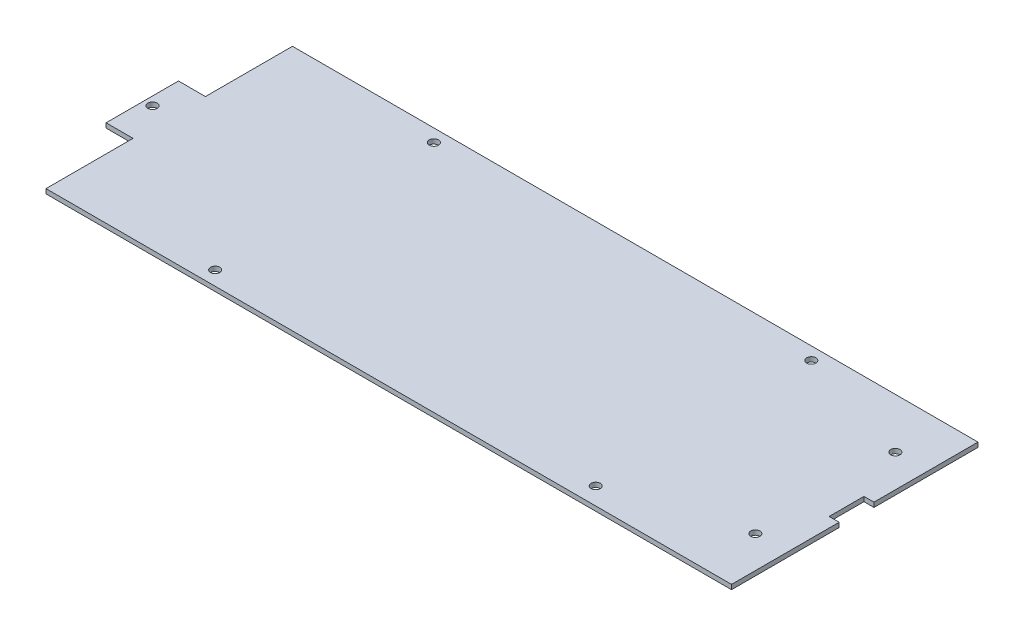
SolidWorks part; units mm, degrees
ref_plane "Front Plane" through (0, 0, 0) normal (0, 0, 1) x (1, 0, 0)
ref_plane "Top Plane" through (0, 0, 0) normal (0, 1, 0) x (1, 0, 0)
ref_plane "Right Plane" through (0, 0, 0) normal (1, 0, 0) x (0, 0, -1)
sketch "Sketch1" plane through (0, 0, 0) normal (0, 1, 0) x (1, 0, 0)
  line L0 (-302.2355, -755.753) -> (-284.7355, -755.753)
  line L1 (-284.7355, -699.253) -> (160.2645, -699.253)
  line L2 (-284.7355, -699.253) -> (-284.7355, -755.753)
  line L5 (-296.7465, -853.0209) -> (-296.7465, -703.1609) construction
  line L6 (-284.7355, -699.253) -> (-286.6881, -713.2193) construction
  line L7 (-302.2355, -755.753) -> (-302.2355, -802.753)
  line L8 (-302.2355, -802.753) -> (-284.7355, -802.753)
  line L9 (-284.7355, -802.753) -> (-284.7355, -859.253)
  line L10 (-284.7355, 31.0446) -> (-284.7355, -755.753) construction
  line L11 (160.2645, -699.253) -> (160.2645, -766.7909)
  line L12 (160.2645, -766.7909) -> (153.7645, -766.7909)
  line L13 (-302.2355, -779.253) -> (-26.2365, -778.0909) construction
  line L14 (161.6735, -769.7909) -> (169.6735, -769.7909) construction
  line L15 (153.7645, -766.7909) -> (153.7645, -789.3909)
  line L16 (153.7645, -789.3909) -> (160.2645, -789.3909)
  line L17 (169.6735, -786.3909) -> (161.6735, -786.3909) construction
  line L18 (160.2645, -789.3909) -> (160.2645, -859.253)
  line L19 (160.2645, -859.253) -> (-284.7355, -859.253)
  line L20 (-194.7355, 72.7736) -> (70.2645, 72.7736) construction
  line L21 (-184.7355, -707.4612) -> (-284.7355, -707.4612) construction
  line L22 (-62.2355, -699.253) -> (-62.2355, -738.3845) construction
  circle A0 centre (-296.7465, -778.0909) radius 3
  circle A1 centre (-194.7355, 72.7736) radius 3
  circle A2 centre (70.2645, 72.7736) radius 3.5
  circle A3 centre (77.426, -1628.1126) radius 3.5
  circle A4 centre (-187.5646, -1630.3441) radius 3
  circle A5 centre (139.1024, -731.753) radius 3
  circle A6 centre (139.4867, -823.0348) radius 3
  circle A7 centre (-184.7355, -707.4612) radius 3
  circle A8 centre (60.2645, -707.4612) radius 3
  circle A9 centre (60.8562, -847.9896) radius 3
  circle A10 centre (-184.1351, -850.0527) radius 3
  point P4 (0, 0)
  dimension "D9" = 6.5
  dimension "D12" = 6
  dimension "D3" = 6
  dimension "D15" = 6
  dimension "D16" = 7
  dimension "D18" = 6
  dimension "D1" = 56.5
  dimension "D2" = 56.5
  dimension "D4" = 3
  dimension "D5" = 3
  dimension "D6" = 17.5
  dimension "D7" = 445
  dimension "D8" = 69.8621
  dimension "D10" = 160
  dimension "D11" = 67.5379
  dimension "D13" = 90
  dimension "D14" = 90
  dimension "D17" = 32.5
  dimension "D19" = 100
extrude "Boss-Extrude1" add sketch "Sketch1" along normal blind 3 from offset 2
